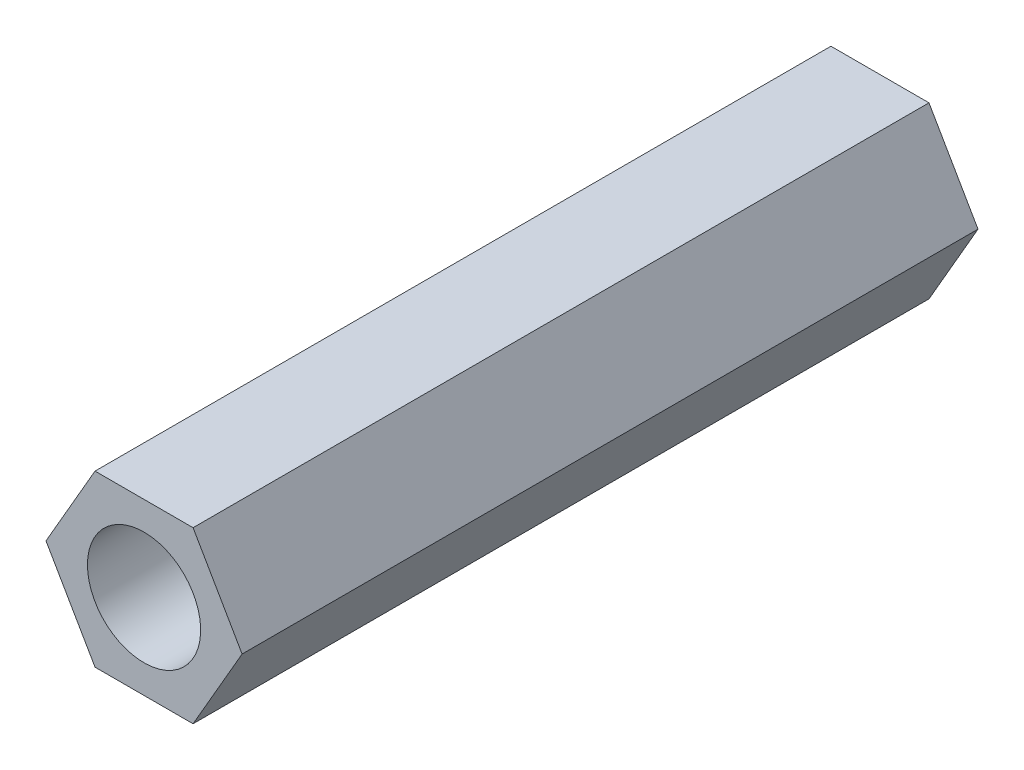
SolidWorks part; units mm, degrees
ref_plane "前视基准面" through (0, 0, 0) normal (0, 0, 1) x (1, 0, 0)
ref_plane "上视基准面" through (0, 0, 0) normal (0, 1, 0) x (1, 0, 0)
ref_plane "右视基准面" through (0, 0, 0) normal (1, 0, 0) x (0, 0, -1)
sketch "草图1" plane through (0, 0, 0) normal (0, 0, 1) x (1, 0, 0)
  line L1 (1.7321, 0) -> (0.866, 1.5)
  line L2 (0.866, 1.5) -> (-0.866, 1.5)
  line L3 (-0.866, 1.5) -> (-1.7321, 0)
  line L4 (-1.7321, 0) -> (-0.866, -1.5)
  line L5 (-0.866, -1.5) -> (0.866, -1.5)
  line L6 (0.866, -1.5) -> (1.7321, 0)
  circle A0 centre (0, 0) radius 1
  circle A1 centre (0, 0) radius 1.5 construction
  dimension "D1" = 2
  dimension "D2" = 3
extrude "凸台-拉伸1" add sketch "草图1" along normal blind 13
